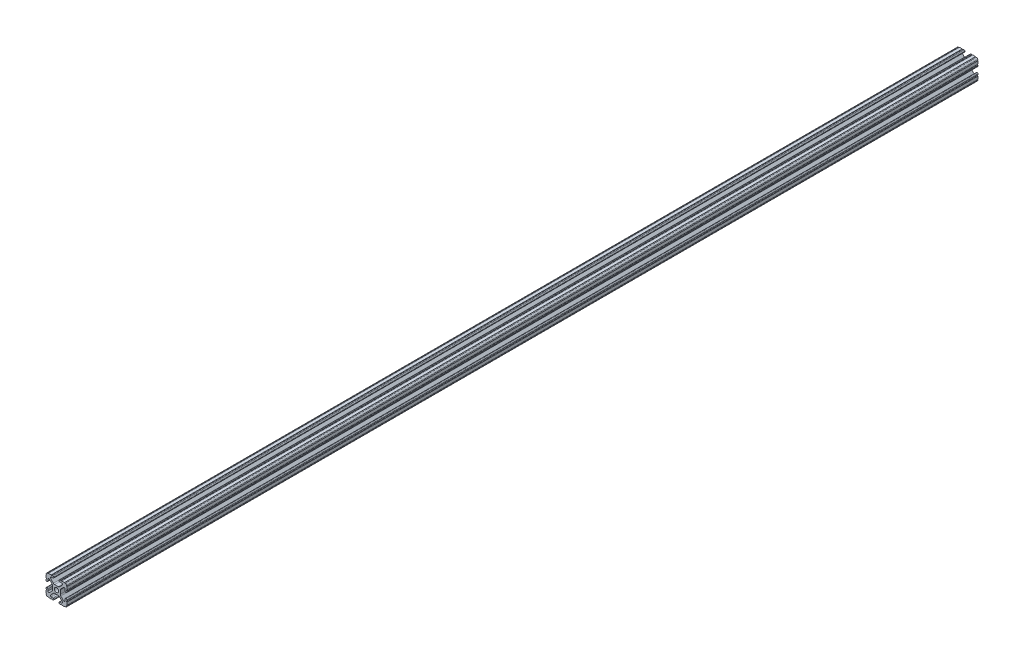
SolidWorks part; units mm, degrees
ref_plane "Front Plane" through (0, 0, 0) normal (0, 0, 1) x (1, 0, 0)
ref_plane "Top Plane" through (0, 0, 0) normal (0, 1, 0) x (1, 0, 0)
ref_plane "Right Plane" through (0, 0, 0) normal (1, 0, 0) x (0, 0, -1)
sketch "Sketch2" plane through (0, 0, 0) normal (0, 0, 1) x (1, 0, 0)
  line L0 (0, 12.7) -> (0, -12.7) construction
  line L1 (-12.7, 0) -> (12.7, 0) construction
  line L2 (3.2512, -12.7) -> (12.7, -12.7)
  line L3 (12.7, -12.7) -> (12.7, -3.2512)
  line L4 (3.2512, -12.7) -> (3.2512, -10.4902)
  line L5 (3.2512, -10.4902) -> (8.9276, -10.4902)
  line L6 (8.9276, -10.4902) -> (3.0856, -4.6482)
  line L7 (0, 0) -> (12.7, -12.7) construction
  line L8 (12.7, -3.2512) -> (10.4902, -3.2512)
  line L9 (10.4902, -3.2512) -> (10.4902, -8.9276)
  line L10 (10.4902, -8.9276) -> (4.6482, -3.0856)
  circle A0 centre (0, 0) radius 2.6035
  arc A1 (6.3485, -10.4902) -> (7.1039, -8.6665) centre (6.3485, -9.4219) ccw construction
  point P8 (0, -4.6482)
  dimension "Center Hole Diameter" = 5.207
  dimension "Rail Height" = 25.4
  dimension "Rail Width" = 25.4
  dimension "T-Slot Width" = 6.5024
  dimension "Slot Inner Width" = 14.8336
  dimension "Thickness" = 2.2098
  dimension "Slot Depth" = 5.842
  dimension "D1" = 2.2098
sketch "Sketch3" plane through (0, 0, 0) normal (1, 0, 0) x (0, 0, -1)
  line L0 (-553.7012, -12.7) -> (553.7012, -12.7) construction
  line L1 (-528.3012, 0) -> (528.3012, 0) construction
  point P5 (-161.0955, -12.7)
  point P6 (-553.7012, -12.7)
sketch "Sketch4" plane through (0, 0, 0) normal (0, 0, 1) x (1, 0, 0)
  line L0 (4.1904, -12.7) -> (10.1173, -12.7)
  line L1 (3.2512, -12.7) -> (12.7, -12.7) construction
  line L2 (3.2512, -12.7) -> (3.2512, -10.4902) construction
  line L3 (3.2512, -10.4902) -> (8.9276, -10.4902) construction
  line L4 (3.2512, -11.4294) -> (3.2512, -11.7608)
  line L5 (4.1904, -10.4902) -> (6.3485, -10.4902)
  line L6 (0, -4.6482) -> (2.164, -4.6482)
  line L7 (8.9276, -10.4902) -> (3.0856, -4.6482) construction
  line L8 (3.7373, -5.2999) -> (7.1039, -8.6665)
  line L9 (12.7, -12.7) -> (12.7, -3.2512) construction
  line L10 (10.4902, -8.9276) -> (4.6482, -3.0856) construction
  line L11 (10.4902, -3.2512) -> (10.4902, -8.9276) construction
  line L12 (10.4902, -6.3485) -> (10.4902, -4.1904)
  line L13 (12.7, -3.2512) -> (10.4902, -3.2512) construction
  line L14 (11.4294, -3.2512) -> (11.7608, -3.2512)
  line L15 (12.7, -4.1904) -> (12.7, -10.1173)
  line L16 (8.6665, -7.1039) -> (5.2999, -3.7373)
  line L17 (4.6482, 0) -> (4.6482, -2.164)
  line L18 (-12.7, 0) -> (12.7, 0) construction
  line L19 (0, -4.6482) -> (0, -2.6035)
  line L20 (0, 12.7) -> (0, -12.7) construction
  line L21 (4.6482, 0) -> (2.6035, 0)
  arc A0 (3.2512, -11.7608) -> (4.1904, -12.7) centre (4.1904, -11.7608) ccw
  arc A2 (3.2512, -11.4294) -> (4.1904, -10.4902) centre (4.1904, -11.4294) cw
  arc A3 (6.3485, -10.4902) -> (7.1039, -8.6665) centre (6.3485, -9.4219) ccw
  arc A4 (2.164, -4.6482) -> (3.7373, -5.2999) centre (2.164, -6.8732) cw
  arc A5 (10.1173, -12.7) -> (12.7, -10.1173) centre (10.1173, -10.1173) ccw
  arc A6 (8.6665, -7.1039) -> (10.4902, -6.3485) centre (9.4219, -6.3485) ccw
  arc A7 (10.4902, -4.1904) -> (11.4294, -3.2512) centre (11.4294, -4.1904) cw
  arc A8 (11.7608, -3.2512) -> (12.7, -4.1904) centre (11.7608, -4.1904) cw
  arc A9 (5.2999, -3.7373) -> (4.6482, -2.164) centre (6.8732, -2.164) cw
  circle A10 centre (0, 0) radius 2.6035 construction
  arc A11 (0, -2.6035) -> (2.6035, 0) centre (0, 0) ccw
  dimension "D1" = 2.5827
  dimension "D2" = 2.225
  dimension "D3" = 0.9392
extrude "Boss-Extrude1" add sketch "Sketch4" along normal up to vertex (553.7012 mm away) from vertex at -553.7012 starting at point (0, -12.7, -553.7012)
sketch "Sketch5" plane through (0, 0, 0) normal (0, 0, 1) x (1, 0, 0)
  line L0 (3.2512, -12.7) -> (12.7, -12.7) construction
  line L1 (4.1904, -10.4902) -> (6.3485, -10.4902) construction
  line L3 (0, 0) -> (12.7, -12.7) construction
  line L4 (6.3485, -10.4902) -> (6.3485, -12.7) construction
  line L5 (8.9276, -10.4902) -> (3.0856, -4.6482) construction
  circle A0 centre (10.3562, -12.7) radius 0.5524
  circle A1 centre (5.796, -12.7) radius 0.5524
  circle A2 centre (12.7, -10.3562) radius 0.5524
  circle A3 centre (12.7, -5.796) radius 0.5524
  point P10 (5.2694, -10.4902)
  point P12 (9.4219, -6.3485)
  dimension "D1" = 1.1049
extrude "Cut-Extrude1" cut sketch "Sketch5" against normal through all both and the other way through all
mirror "Mirror1" about plane through (0, 0, 0) normal (1, 0, 0) of bodies 137 134
mirror "Mirror2" about plane through (0, 0, 0) normal (0, 1, 0) of bodies 135
equation "\"D1@Sketch2\"=\"Thickness@Sketch2\""
equation "\"D2@Sketch4\"=\"Slot Inner Width@Sketch2\"*0.15"
equation "\"D1@Sketch4\"=\"D3@Sketch4\"*2.75"
equation "\"D3@Sketch4\"=\"Thickness@Sketch2\"*0.425"
equation "\"D1@Sketch5\"=\"Thickness@Sketch2\"*0.5"
equation "\"D1@Boss-Extrude1\"=\"Length@Sketch3\""
